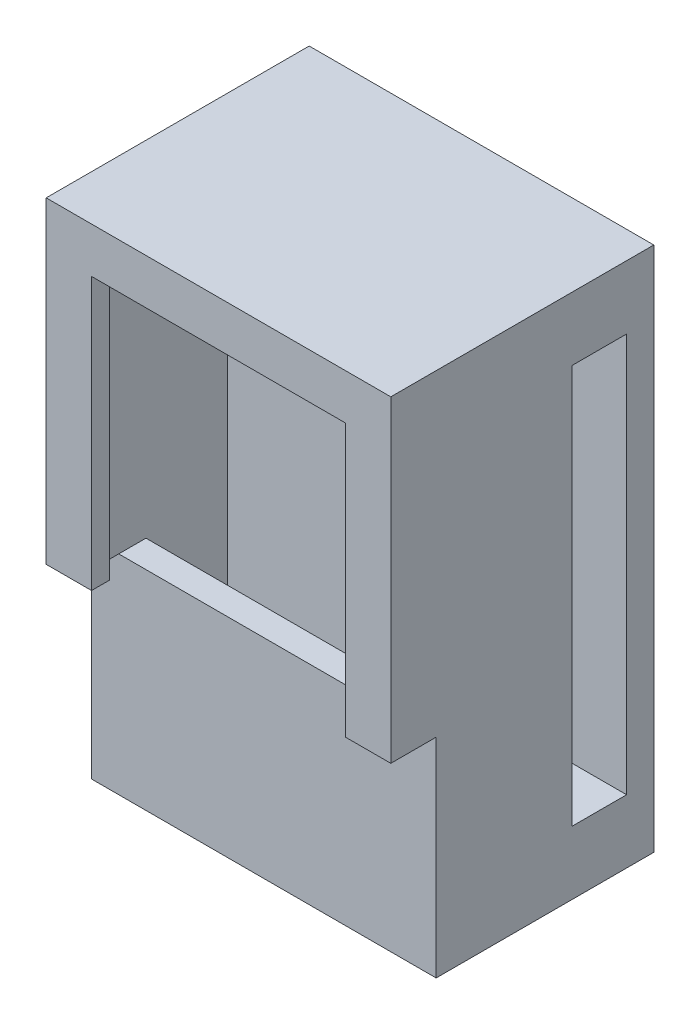
SolidWorks part; units mm, degrees
ref_plane "Alzado" through (0, 0, 0) normal (0, 0, 1) x (1, 0, 0)
ref_plane "Planta" through (0, 0, 0) normal (0, 1, 0) x (1, 0, 0)
ref_plane "Vista lateral" through (0, 0, 0) normal (1, 0, 0) x (0, 0, -1)
sketch "Croquis1" plane through (0, 0, 0) normal (0, 0, 1) x (1, 0, 0)
  line L1 (-31.723, 20.4398) -> (-12.723, 20.4398)
  line L2 (-31.723, 20.4398) -> (-31.723, -8.5602)
  line L3 (-31.723, -8.5602) -> (-12.723, -8.5602)
  line L4 (-12.723, 20.4398) -> (-12.723, -8.5602)
  dimension "D1" = 29
  dimension "D2" = 19
extrude "Saliente-Extruir1" add sketch "Croquis1" along normal blind 6
sketch "Croquis2" plane through (0, 0, 6) normal (0, 0, 1) x (1, 0, 0)
  line L0 (-31.723, -8.5602) -> (-31.723, 2.9398)
  line L1 (-31.723, 20.4398) -> (-31.723, -8.5602) construction
  line L2 (-31.723, 2.9398) -> (-30.223, 2.9398)
  line L3 (-30.223, 2.9398) -> (-30.223, -7.0602)
  line L4 (-30.223, -7.0602) -> (-14.223, -7.0602)
  line L5 (-14.223, -7.0602) -> (-14.223, 2.9398)
  line L6 (-14.223, 2.9398) -> (-12.723, 2.9398)
  line L7 (-12.723, -8.5602) -> (-12.723, 20.4398) construction
  line L8 (-12.723, 2.9398) -> (-12.723, -8.5602)
  line L9 (-12.723, -8.5602) -> (-31.723, -8.5602)
  dimension "D1" = 1.5
  dimension "D2" = 1.5
  dimension "D3" = 10
extrude "Saliente-Extruir2" add sketch "Croquis2" along normal blind 4.5
sketch "Croquis3" plane through (0, 0, 10.5) normal (0, 0, 1) x (1, 0, 0)
  line L1 (-31.723, 2.9398) -> (-12.723, 2.9398)
  line L2 (-31.723, 2.9398) -> (-31.723, -8.5602)
  line L3 (-31.723, -8.5602) -> (-12.723, -8.5602)
  line L4 (-12.723, 2.9398) -> (-12.723, -8.5602)
extrude "Saliente-Extruir3" add sketch "Croquis3" along normal blind 1.5
sketch "Croquis4" plane through (0, -8.5602, 0) normal (0, -1, 0) x (1, 0, 0)
  line L1 (-27.223, 9.3) -> (-15.223, 9.3)
  line L2 (-27.223, 9.3) -> (-27.223, 5.3)
  line L3 (-27.223, 5.3) -> (-15.223, 5.3)
  line L4 (-15.223, 9.3) -> (-15.223, 5.3)
  line L5 (-31.723, 12) -> (-31.723, 0) construction
  line L6 (-31.723, 12) -> (-12.723, 12) construction
  dimension "D1" = 2.7
  dimension "D2" = 4
  dimension "D3" = 12
  dimension "D4" = 4.5
extrude "Cortar-Extruir1" cut sketch "Croquis4" against normal blind 5
sketch "Croquis5" plane through (0, 0, 6) normal (0, 0, 1) x (1, 0, 0)
  line L0 (-30.223, 2.9398) -> (-31.723, 2.9398)
  line L1 (-31.723, 2.9398) -> (-31.723, 20.4398)
  line L2 (-31.723, 20.4398) -> (-12.723, 20.4398)
  line L3 (-12.723, 20.4398) -> (-12.723, 2.9398)
  line L4 (-12.723, 2.9398) -> (-14.223, 2.9398)
  line L5 (-14.223, 2.9398) -> (-14.223, 18.9398)
  line L6 (-14.223, 18.9398) -> (-30.223, 18.9398)
  line L7 (-30.223, 18.9398) -> (-30.223, 2.9398)
  dimension "D1" = 1.5
extrude "Saliente-Extruir4" add sketch "Croquis5" along normal blind 7.5
sketch "Croquis6" plane through (0, 0, 13.5) normal (0, 0, 1) x (1, 0, 0)
  line L6 (-29.223, 2.9398) -> (-31.723, 2.9398)
  line L7 (-31.723, 2.9398) -> (-31.723, 20.4398)
  line L8 (-31.723, 20.4398) -> (-12.723, 20.4398)
  line L9 (-15.223, 17.9398) -> (-15.223, 2.9398)
  line L10 (-29.223, 17.9398) -> (-15.223, 17.9398)
  line L11 (-29.223, 2.9398) -> (-29.223, 17.9398)
  line L12 (-15.223, 17.9398) -> (-15.223, 2.9398)
  line L13 (-29.223, 17.9398) -> (-15.223, 17.9398)
  line L14 (-29.223, 2.9398) -> (-29.223, 17.9398)
  line L15 (-12.723, 20.4398) -> (-12.723, 2.9398)
  line L16 (-12.723, 2.9398) -> (-15.223, 2.9398)
  dimension "D1" = 1
extrude "Saliente-Extruir5" add sketch "Croquis6" along normal blind 1
sketch "Croquis7" plane through (-12.723, 0, 0) normal (1, 0, 0) x (0, 0, -1)
  line L1 (-4.5, -5.0602) -> (-1.5, -5.0602)
  line L2 (-4.5, -5.0602) -> (-4.5, 16.9398)
  line L3 (-4.5, 16.9398) -> (-1.5, 16.9398)
  line L4 (-1.5, -5.0602) -> (-1.5, 16.9398)
  line L5 (0, -8.5602) -> (0, 20.4398) construction
  dimension "D1" = 3
  dimension "D2" = 22
  dimension "D3" = 1.5
extrude "Cortar-Extruir2" cut sketch "Croquis7" against normal up to vertex
